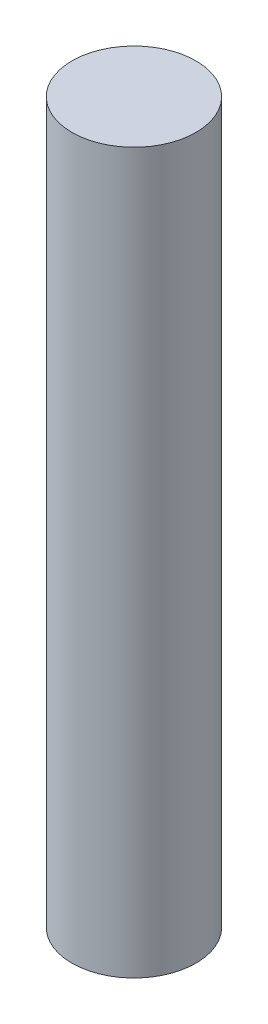
SolidWorks part; units mm, degrees
ref_plane "Front Plane" through (0, 0, 0) normal (0, 0, 1) x (1, 0, 0)
ref_plane "Top Plane" through (0, 0, 0) normal (0, 1, 0) x (1, 0, 0)
ref_plane "Right Plane" through (0, 0, 0) normal (1, 0, 0) x (0, 0, -1)
sketch "Sketch1" plane through (0, 0, 0) normal (0, 1, 0) x (1, 0, 0)
  circle A0 centre (0, 0) radius 4.7625
  dimension "D1" = 9.525
extrude "Boss-Extrude1" add sketch "Sketch1" against normal blind 9.525
sketch "Sketch2" plane through (0, -9.525, 0) normal (0, -1, 0) x (-1, 0, 0)
  circle A0 centre (0, 0) radius 4.7625
  dimension "D1" = 9.525
extrude "Boss-Extrude2" add sketch "Sketch2" along normal blind 45.72
